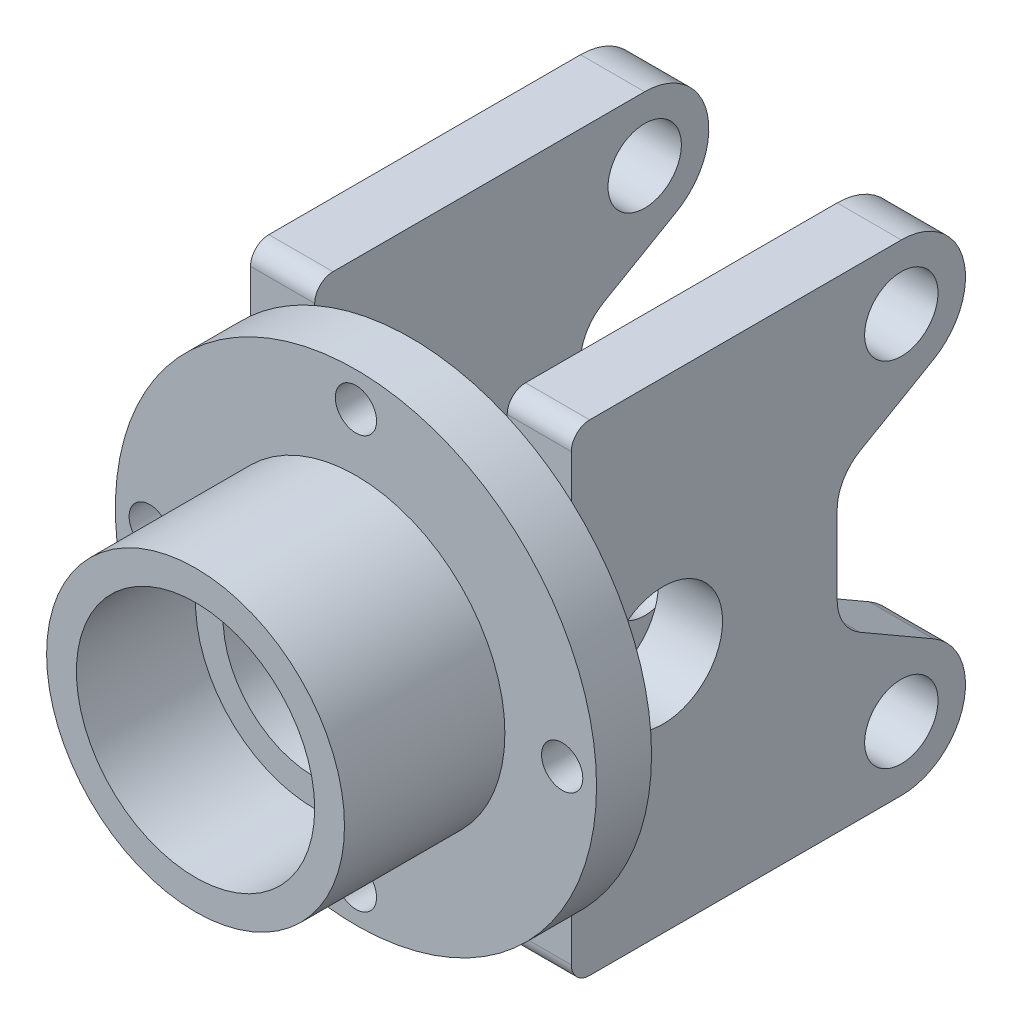
SolidWorks part; units mm, degrees
ref_plane "前视基准面" through (0, 0, 0) normal (0, 0, 1) x (1, 0, 0)
ref_plane "上视基准面" through (0, 0, 0) normal (0, 1, 0) x (1, 0, 0)
ref_plane "右视基准面" through (0, 0, 0) normal (1, 0, 0) x (0, 0, -1)
sketch "草图1" plane through (0, 0, 0) normal (0, 0, 1) x (1, 0, 0)
  circle A0 centre (0, 0) radius 52.5
  dimension "D1" = 105
extrude "凸台-拉伸1" add sketch "草图1" against normal blind 12
sketch "草图2" plane through (0, 0, 0) normal (0, 0, 1) x (1, 0, 0)
  circle A0 centre (0, 0) radius 32.5
  dimension "D1" = 65
extrude "凸台-拉伸2" add sketch "草图2" along normal blind 35
sketch "草图3" plane through (0, 0, 35) normal (0, 0, 1) x (1, 0, 0)
  circle A0 centre (0, 0) radius 26
  dimension "D1" = 52
extrude "切除-拉伸1" cut sketch "草图3" against normal blind 26
sketch "草图4" plane through (0, 0, 9) normal (0, 0, 1) x (1, 0, 0)
  circle A0 centre (0, 0) radius 20
  dimension "D1" = 40
extrude "切除-拉伸2" cut sketch "草图4" against normal blind 21
sketch "草图5" plane through (0, 0, 0) normal (1, 0, 0) x (0, 0, -1)
  line L0 (25.85, 0) -> (-25.85, 0) construction
  line L1 (12, -52.5) -> (12, 52.5) construction
  line L2 (84, -52.5) -> (16, -52.5)
  line L3 (98, -38.5) -> (98, 38.5) construction
  line L4 (84, 52.5) -> (16, 52.5)
  line L5 (12, -48.5) -> (12, 48.5)
  line L6 (94.2998, -47.9823) -> (12, 52.5) construction
  line L7 (94.2998, 47.9823) -> (12, -52.5) construction
  line L8 (98, 52.5) -> (84, 52.5) construction
  line L9 (98, 52.5) -> (94.2998, 47.9823) construction
  line L10 (98, 38.5) -> (98, 52.5) construction
  line L11 (91, 26.3756) -> (75, 17.138)
  line L12 (70, 8.4778) -> (70, -8.4778)
  line L13 (0, 0) -> (70, 0) construction
  line L14 (91, -26.3756) -> (75, -17.138)
  line L15 (98, -52.5) -> (98, -38.5) construction
  line L16 (98, -52.5) -> (94.2998, -47.9823) construction
  line L17 (98, -52.5) -> (84, -52.5) construction
  arc A0 (91, 26.3756) -> (84, 52.5) centre (84, 38.5) ccw
  arc A1 (91, -26.3756) -> (84, -52.5) centre (84, -38.5) cw
  arc A2 (84, 52.5) -> (76.7326, 26.534) centre (84, 38.5) ccw construction
  arc A3 (76.7326, 26.534) -> (91, 26.3756) centre (84, 38.5) ccw construction
  arc A4 (84, -52.5) -> (76.7326, -26.534) centre (84, -38.5) cw construction
  arc A5 (76.7326, -26.534) -> (91, -26.3756) centre (84, -38.5) cw construction
  circle A6 centre (84, 38.5) radius 8
  circle A7 centre (84, -38.5) radius 8
  circle A8 centre (32, 0) radius 13
  arc A9 (75, -17.138) -> (70, -8.4778) centre (80, -8.4778) cw
  arc A10 (75, 17.138) -> (70, 8.4778) centre (80, 8.4778) ccw
  arc A11 (16, -52.5) -> (12, -48.5) centre (16, -48.5) cw
  arc A12 (16, 52.5) -> (12, 48.5) centre (16, 48.5) ccw
  point P2 (55, 0)
  point P32 (70, -14.2513)
  point P35 (70, 14.2513)
  dimension "D1" = 28
  dimension "D2" = 16
  dimension "D3" = 16
  dimension "D4" = 26
  dimension "D9" = 10
  dimension "D10" = 4
  dimension "D5" = 20
  dimension "D6" = 72
  dimension "D7" = 77
  dimension "D8" = 60
extrude "凸台-拉伸3" add sketch "草图5" along normal mid plane 70
sketch "草图6" plane through (0, -52.5, 0) normal (0, -1, 0) x (1, 0, 0)
  line L0 (0, -57.75) -> (0, 57.75) construction
  line L1 (21, -113.2439) -> (-21, -113.2439)
  line L2 (21, -113.2439) -> (21, -12)
  line L3 (21, -12) -> (-21, -12)
  line L4 (-21, -113.2439) -> (-21, -12)
  line L5 (21, -113.2439) -> (-21, -12) construction
  line L6 (21, -12) -> (-21, -113.2439) construction
  line L7 (-20.0998, -12) -> (20.0998, -12) construction
  point P0 (0, -62.622)
  dimension "D1" = 42
extrude "切除-拉伸3" cut sketch "草图6" against normal through all
sketch "草图7" plane through (0, 0, -12) normal (0, 0, -1) x (-1, 0, 0)
  line L0 (57.75, 0) -> (-57.75, 0) construction
  circle A0 centre (-45, 0) radius 4.5
  dimension "D1" = 9
  dimension "D2" = 45
extrude "切除-拉伸4" cut sketch "草图7" against normal through all
pattern_circular "阵列(圆周)1" count 4 over 360 about axis through (0, 0, 0) along (0, 0, 1) of "切除-拉伸4"
